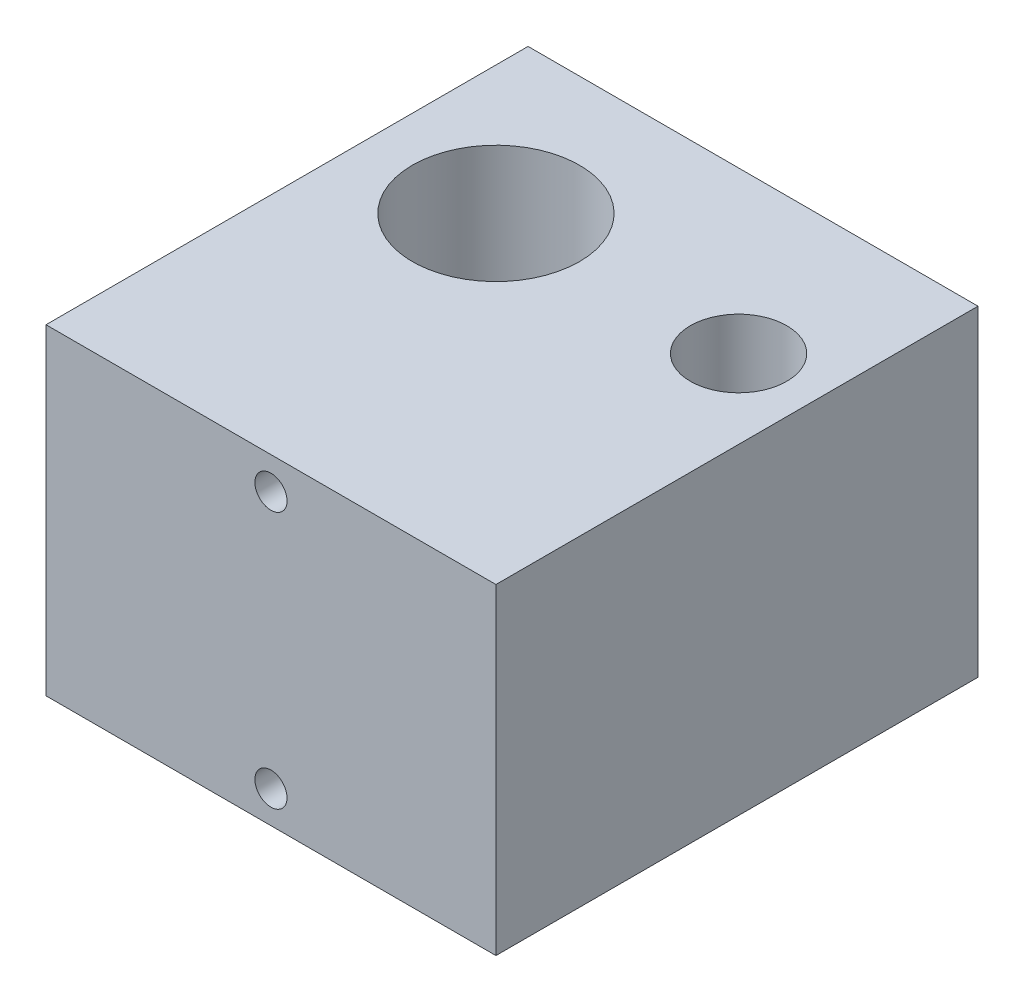
SolidWorks part; units mm, degrees
ref_plane "Front Plane" through (0, 0, 0) normal (0, 0, 1) x (1, 0, 0)
ref_plane "Top Plane" through (0, 0, 0) normal (0, 1, 0) x (1, 0, 0)
ref_plane "Right Plane" through (0, 0, 0) normal (1, 0, 0) x (0, 0, -1)
sketch "Sketch1" plane through (0, 0, 0) normal (0, 0, 1) x (1, 0, 0)
  line L1 (35, -25) -> (-35, -25)
  line L2 (35, -25) -> (35, 25)
  line L3 (35, 25) -> (-35, 25)
  line L4 (-35, -25) -> (-35, 25)
  line L5 (35, -25) -> (-35, 25) construction
  line L6 (35, 25) -> (-35, -25) construction
  point P0 (0, 0)
  dimension "D1" = 70
  dimension "D2" = 50
extrude "Boss-Extrude1" add sketch "Sketch1" along normal blind 75
sketch "Sketch2" plane through (0, 25, 0) normal (0, 1, 0) x (1, 0, 0)
  line L0 (-35, -25) -> (35, -25) construction
  line L1 (-35, -75) -> (-35, 0) construction
  line L2 (35, -75) -> (35, 0) construction
  line L3 (0, 0) -> (0, -75) construction
  line L4 (35, -75) -> (-35, -75) construction
  line L5 (35, 0) -> (-35, 0) construction
  circle A0 centre (22.75, -25) radius 7.5
  circle A1 centre (-15, -25) radius 13
  dimension "D1" = 15
  dimension "D2" = 26
  dimension "D3" = 25
  dimension "D4" = 20
  dimension "D5" = 37.75
extrude "Cut-Extrude1" cut sketch "Sketch2" against normal up to next
sketch "Sketch3" plane through (0, 0, 75) normal (0, 0, 1) x (1, 0, 0)
  line L0 (0, 25) -> (0, -25) construction
  line L1 (35, 25) -> (-35, 25) construction
  line L2 (-35, -25) -> (35, -25) construction
  line L3 (-35, 0) -> (35, 0) construction
  line L4 (-35, 25) -> (-35, -25) construction
  line L5 (35, -25) -> (35, 25) construction
  circle A0 centre (0, -20) radius 2.5
  circle A1 centre (0, 20) radius 2.5
  dimension "D1" = 5
  dimension "D2" = 40
extrude "Cut-Extrude2" cut sketch "Sketch3" against normal blind 20
